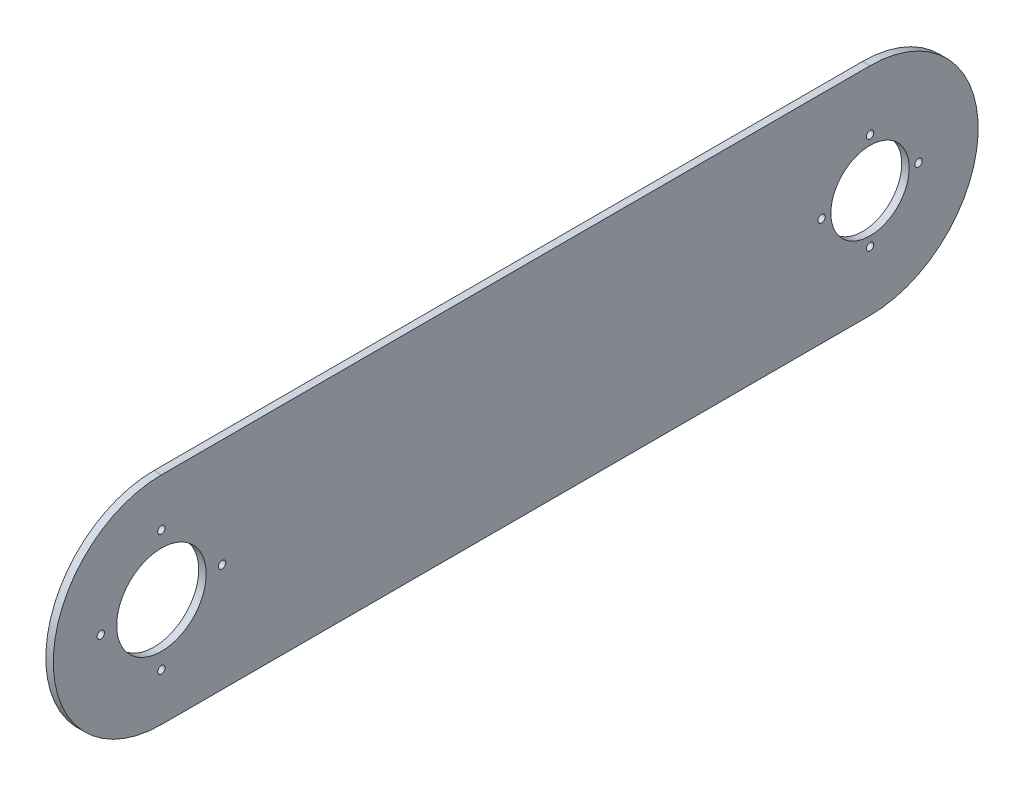
SolidWorks part; units mm, degrees
material "2024-T4"
ref_plane "Front Plane" through (0, 0, 0) normal (0, 0, 1) x (1, 0, 0)
ref_plane "Top Plane" through (0, 0, 0) normal (0, 1, 0) x (1, 0, 0)
ref_plane "Right Plane" through (0, 0, 0) normal (1, 0, 0) x (0, 0, -1)
sketch "Sketch1" plane through (0, 0, 0) normal (1, 0, 0) x (0, 0, -1)
  line L0 (0, 0) -> (380, 0) construction
  line L1 (0, 58) -> (380, 58)
  line L2 (0, -58) -> (380, -58)
  circle A0 centre (0, 0) radius 24
  arc A1 (0, 58) -> (0, -58) centre (0, 0) ccw
  arc A2 (380, -58) -> (380, 58) centre (380, 0) ccw
  circle A3 centre (380, 0) radius 24
  point P3 (190, 0)
  dimension "D1" = 58
  dimension "D2" = 48
  dimension "D3" = 380
extrude "Boss-Extrude1" add sketch "Sketch1" along normal blind 4
sketch "Sketch2" plane through (0, 0, 0) normal (-1, 0, 0) x (0, 0, 1)
  circle A0 centre (0, 0) radius 29
  dimension "D1" = 58
extrude "Cut-Extrude1" [suppressed] cut sketch "Sketch2" against normal blind 2
sketch "Sketch3" plane through (0, 0, 0) normal (-1, 0, 0) x (0, 0, 1)
  line L0 (58, 0) -> (58, 58) construction
  line L1 (58, 58) -> (-67, 58) construction
  line L2 (-380, 58) -> (0, 58) construction
  line L3 (0, -58) -> (-380, -58) construction
  line L4 (-67, 58) -> (-71, 58) construction
  line L5 (-67, 58) -> (-67, -58) construction
  line L6 (-67, -58) -> (-71, -58) construction
  line L7 (-71, 58) -> (-71, -58) construction
  line L8 (-67, 0) -> (-60, 0) construction
  line L9 (-69, 58) -> (-69, 36.6334) construction
  arc A0 (0, -58) -> (0, 58) centre (0, 0) ccw construction
  circle A1 centre (-60, 51) radius 2
  circle A2 centre (-78, 51) radius 2
  circle A3 centre (-60, -51) radius 2
  circle A4 centre (-78, -51) radius 2
  dimension "D3" = 4
  dimension "D1" = 125
  dimension "D2" = 4
  dimension "D4" = 7
  dimension "D5" = 7
extrude "Cut-Extrude2" [suppressed] cut sketch "Sketch3" against normal through all
sketch "Sketch4" plane through (0, 0, 0) normal (-1, 0, 0) x (0, 0, 1)
  circle A0 centre (0, 0) radius 32.5 construction
  circle A1 centre (0, 32.5) radius 2
  circle A2 centre (32.5, 0) radius 2
  circle A3 centre (0, -32.5) radius 2
  circle A4 centre (-32.5, 0) radius 2
  point P13 (0, 0)
  dimension "D1" = 65
  dimension "D2" = 4
  dimension "D3" = 4
extrude "Cut-Extrude3" cut sketch "Sketch4" against normal through all
sketch "Sketch5" [suppressed] plane through (0, 0, 0) normal (-1, 0, 0) x (0, 0, 1)
  circle A0 centre (0, 0) radius 24 construction
  circle A1 centre (0, 0) radius 24
  circle A2 centre (0, 0) radius 12.5
  dimension "D1" = 25
extrude "Boss-Extrude2" [suppressed] add sketch "Sketch5" against normal up to surface (4 mm away)
sketch "Sketch6" [suppressed] plane through (4, 0, 0) normal (1, 0, 0) x (0, 0, -1)
  circle A0 centre (0, 0) radius 13.5
  dimension "D1" = 27
extrude "Cut-Extrude4" [suppressed] cut sketch "Sketch6" against normal blind 2
sketch "Sketch7" plane through (0, 0, 0) normal (-1, 0, 0) x (0, 0, 1)
  circle A1 centre (-380, 0) radius 21
  circle A2 centre (-380, 0) radius 24 construction
  circle A3 centre (-380, 0) radius 24
  dimension "D1" = 42
extrude "Boss-Extrude3" add sketch "Sketch7" against normal up to surface (4 mm away) up to face at (4, 32.5, 2)
sketch "Sketch8" plane through (0, 0, 0) normal (-1, 0, 0) x (0, 0, 1)
  circle A0 centre (-380, 0) radius 26 construction
  circle A1 centre (-380, 26) radius 2
  circle A2 centre (-354, 0) radius 2
  circle A3 centre (-380, -26) radius 2
  circle A4 centre (-406, 0) radius 2
  point P14 (-380, 0)
  dimension "D1" = 52
  dimension "D2" = 4
  dimension "D3" = 4
extrude "Cut-Extrude5" cut sketch "Sketch8" against normal through all
